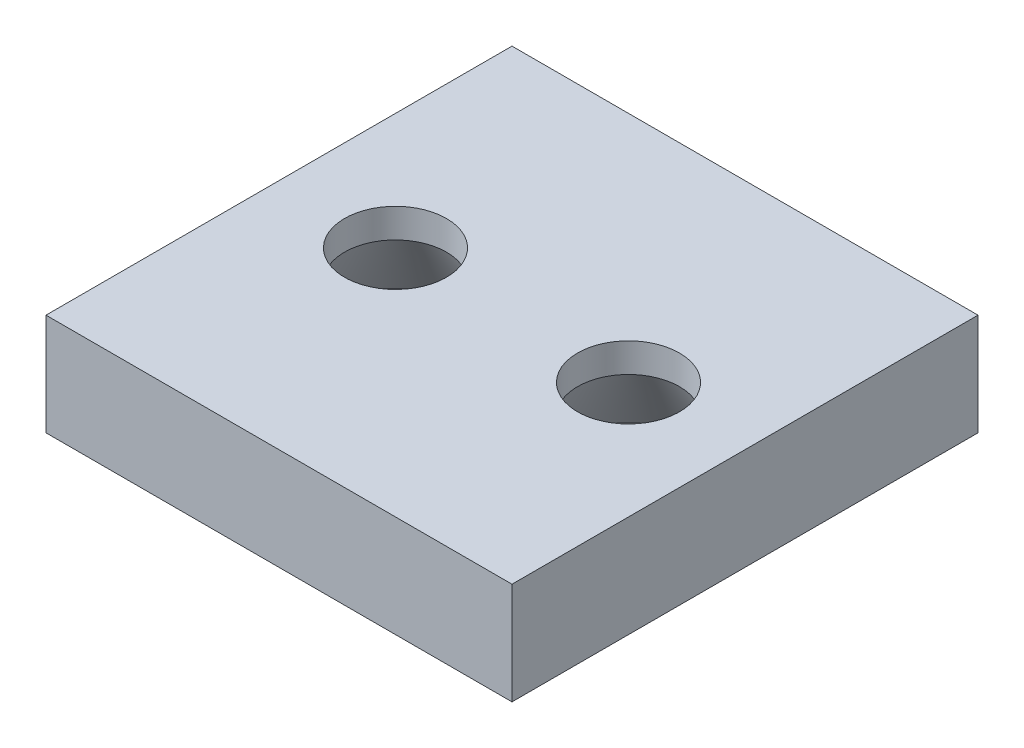
SolidWorks part; units mm, degrees
ref_plane "Front Plane" through (0, 0, 0) normal (0, 0, 1) x (1, 0, 0)
ref_plane "Top Plane" through (0, 0, 0) normal (0, 1, 0) x (1, 0, 0)
ref_plane "Right Plane" through (0, 0, 0) normal (1, 0, 0) x (0, 0, -1)
sketch "Sketch1" plane through (0, 0, 0) normal (0, 1, 0) x (1, 0, 0)
  line L1 (-16, 16) -> (16, 16)
  line L2 (-16, 16) -> (-16, -16)
  line L3 (-16, -16) -> (16, -16)
  line L4 (16, 16) -> (16, -16)
  line L5 (-16, 16) -> (16, -16) construction
  line L6 (-16, -16) -> (16, 16) construction
  point P0 (0, 0)
extrude "Boss-Extrude1" add sketch "Sketch1" along normal blind 7
hole_wizard "CSK for M1.6 Countersunk Flat Head Screw1" positions "3DSketch1" profile "Sketch3" countersink size "M1.6" standard "ISO" end condition through all
sketch3d "3DSketch1"
  point P0 (8, 0, 0)
sketch "Sketch3" plane through (8, 0, 0) normal (1, 0, 0) x (0, 0, -1)
  line L0 (0, 0) -> (0, 7)
  line L1 (0, 7) -> (3.5, 7)
  line L2 (3.5, 7) -> (3.5, 4.9998)
  line L3 (3.5, 4.9998) -> (6.5, 0)
  line L5 (6.5, 0) -> (0, 0)
  line L6 (-3.5, 4.9998) -> (-6.5, 0) construction
  line L11 (0, -6.35) -> (0, 107.95) construction
  dimension "Thru Hole Dia." = 7
  dimension "Thru Hole Depth" = 7
  dimension "Near C'Sink Dia." = 13
  dimension "Near C'Sink Angle" = 61.93
pattern_linear "LPattern2" count 2 spacing 16 along (-1, 0, 0) of "CSK for M1.6 Countersunk Flat Head Screw1"
